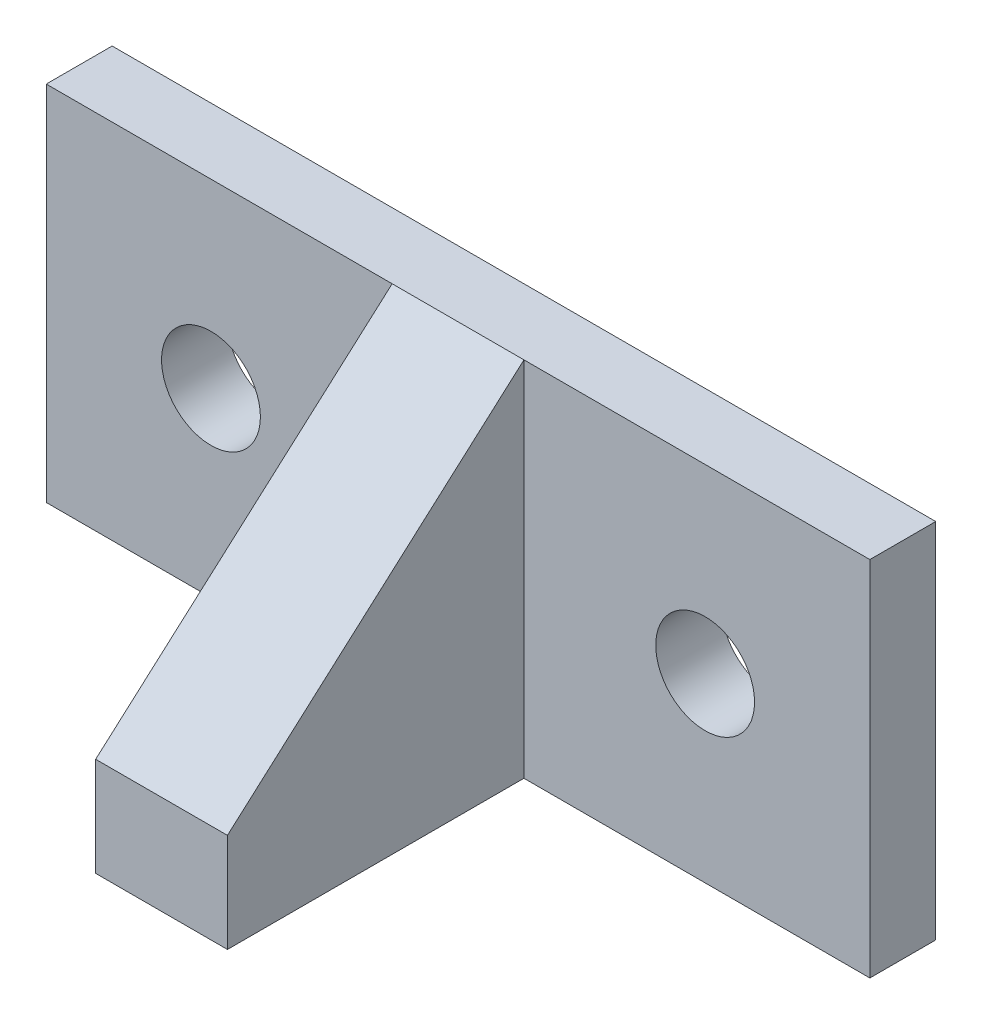
SolidWorks part; units mm, degrees
ref_plane "Płaszczyzna przednia" through (0, 0, 0) normal (0, 0, 1) x (1, 0, 0)
ref_plane "Płaszczyzna górna" through (0, 0, 0) normal (0, 1, 0) x (1, 0, 0)
ref_plane "Płaszczyzna prawa" through (0, 0, 0) normal (1, 0, 0) x (0, 0, -1)
sketch "Szkic1" plane through (0, 0, 0) normal (0, 0, 1) x (1, 0, 0)
  line L1 (-62.5, 27.5) -> (62.5, 27.5)
  line L2 (-62.5, 27.5) -> (-62.5, -27.5)
  line L3 (-62.5, -27.5) -> (62.5, -27.5)
  line L4 (62.5, 27.5) -> (62.5, -27.5)
  line L5 (-62.5, 27.5) -> (62.5, -27.5) construction
  line L6 (-62.5, -27.5) -> (62.5, 27.5) construction
  circle A0 centre (-37.5, 0) radius 7.5
  circle A1 centre (37.5, 0) radius 7.5
  point P0 (0, 0)
  point P10 (0, 0)
  point P11 (0, 0)
  dimension "D3" = 15
  dimension "D4" = 15
  dimension "D1" = 55
  dimension "D2" = 125
  dimension "D5" = 75
  dimension "D6" = 37.5
extrude "Dodanie-wyciągnięcie1" add sketch "Szkic1" along normal blind 10
sketch "Szkic2" plane through (0, 0, 10) normal (0, 0, 1) x (1, 0, 0)
  line L1 (-10, 27.5) -> (10, 27.5)
  line L2 (-10, 27.5) -> (-10, -27.5)
  line L3 (-10, -27.5) -> (10, -27.5)
  line L4 (10, 27.5) -> (10, -27.5)
  line L5 (-10, 27.5) -> (10, -27.5) construction
  line L6 (-10, -27.5) -> (10, 27.5) construction
  point P0 (0, 0)
  dimension "D1" = 55
  dimension "D2" = 20
extrude "Dodanie-wyciągnięcie2" add sketch "Szkic2" along normal blind 45
sketch "Szkic3" plane through (10, 0, 0) normal (1, 0, 0) x (0, 0, -1)
  line L0 (-10, 27.5) -> (-55, -12.5)
  line L1 (-55, -27.5) -> (-55, 27.5) construction
  line L2 (-55, -12.5) -> (-55, -27.5)
  line L3 (-55, -27.5) -> (-10, -27.5)
  line L4 (-10, -27.5) -> (-10, 27.5)
  line L5 (-55, 27.5) -> (-10, 27.5) construction
  line L6 (-55, -27.5) -> (-55, 27.5)
  line L7 (-55, 27.5) -> (-10, 27.5)
  line M6 (-10, 27.5) -> (-55, 27.5)
  line M7 (-55, 27.5) -> (-55, -27.5)
  dimension "D1" = 15
extrude "Wytnij-wyciągnięcie1" cut sketch "Szkic3" against normal blind 45 contours L0 M6 M7
